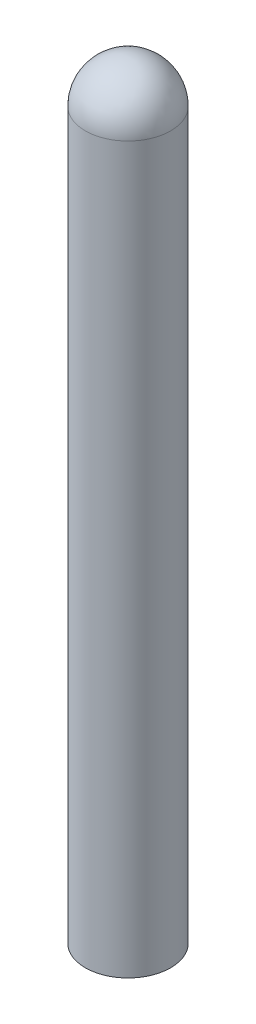
SolidWorks part; units mm, degrees
material "Plain Carbon Steel"
ref_plane "Front Plane" through (0, 0, 0) normal (0, 0, 1) x (1, 0, 0)
ref_plane "Top Plane" through (0, 0, 0) normal (0, 1, 0) x (1, 0, 0)
ref_plane "Right Plane" through (0, 0, 0) normal (1, 0, 0) x (0, 0, -1)
sketch "Sketch2" plane through (0, 0, 0) normal (0, 1, 0) x (1, 0, 0)
  circle A0 centre (0, 0) radius 3.175
  dimension "D1" = 6.35
extrude "Boss-Extrude1" add sketch "Sketch2" along normal blind 57.15
fillet "Fillet1" radius 3.175 1 edges at (0, 57.15, 3.175)
